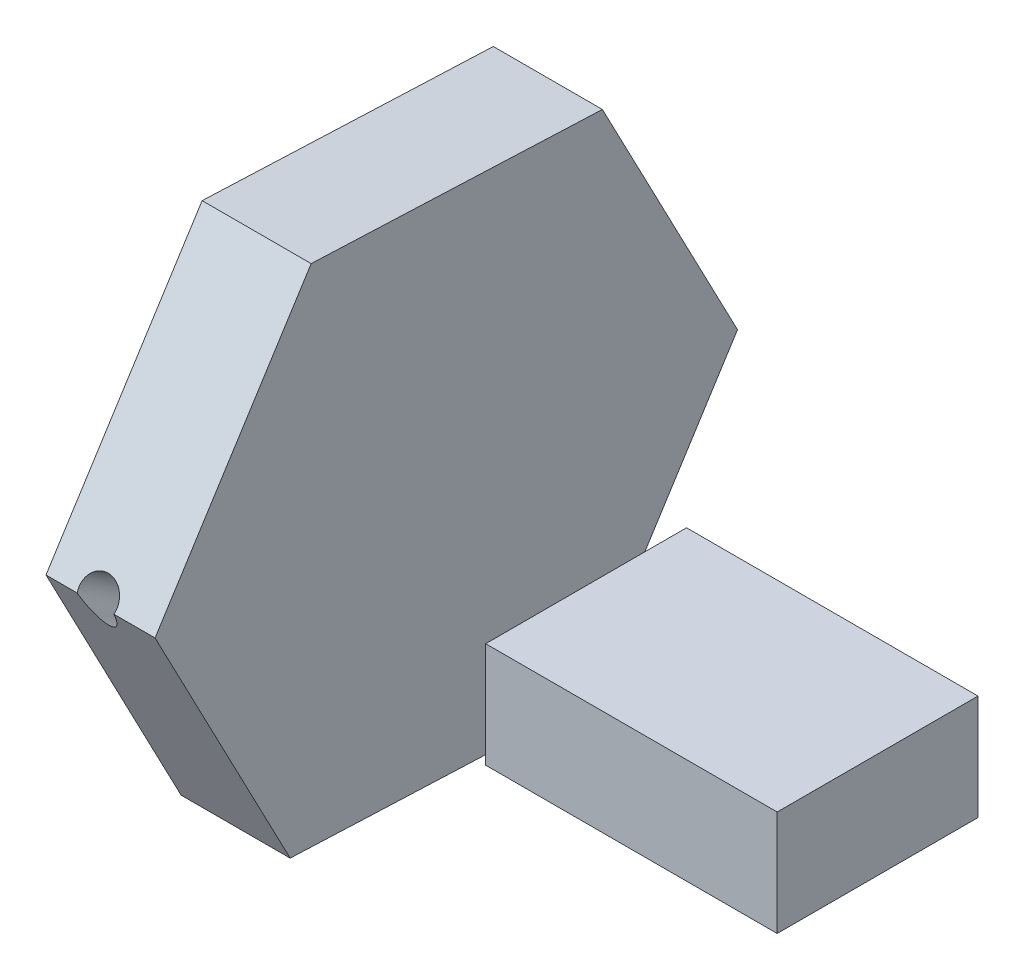
SolidWorks part; units mm, degrees
ref_plane "Front Plane" through (0, 0, 0) normal (0, 0, 1) x (1, 0, 0)
ref_plane "Top Plane" through (0, 0, 0) normal (0, 1, 0) x (1, 0, 0)
ref_plane "Right Plane" through (0, 0, 0) normal (1, 0, 0) x (0, 0, -1)
sketch "Sketch1" plane through (0, 0, 0) normal (1, 0, 0) x (0, 0, -1)
  line L1 (-111.7617, -39.181) -> (98.2408, -39.181)
  line L2 (-111.7617, -39.181) -> (-111.7617, 70.8757)
  line L3 (-111.7617, 70.8757) -> (98.2408, 70.8757)
  line L4 (98.2408, -39.181) -> (98.2408, 70.8757)
  point P4 (-111.7617, -39.181)
sketch "Sketch2" plane through (0, 0, 0) normal (1, 0, 0) x (0, 0, -1)
  line L0 (0, 0) -> (-152.9841, 236.2942) construction
  line L1 (10.2491, 493.7004) -> (-294.2878, 506.3614)
  line L2 (-294.2878, 506.3614) -> (-457.521, 248.9552)
  line L3 (-457.521, 248.9552) -> (-316.2173, -21.112)
  line L4 (-316.2173, -21.112) -> (-11.6804, -33.773)
  line L5 (-11.6804, -33.773) -> (151.5528, 223.6332)
  line L6 (151.5528, 223.6332) -> (10.2491, 493.7004)
  circle A0 centre (-152.9841, 236.2942) radius 263.9645 construction
  point P1 (-41.5239, 165.6121)
  dimension "D1" = 304.8
extrude "Boss-Extrude1" add sketch "Sketch1" along normal blind 304.8
extrude "Boss-Extrude2" add sketch "Sketch2" against normal blind 114.046 separate body
sketch "Sketch3" plane through (0, 278.3246, 438.8965) normal (0, 0.5355, 0.8445) x (1, 0, 0)
  circle A0 centre (-62.2641, -29.8278) radius 19.8471
extrude "Cut-Extrude1" cut sketch "Sketch3" against normal through all
